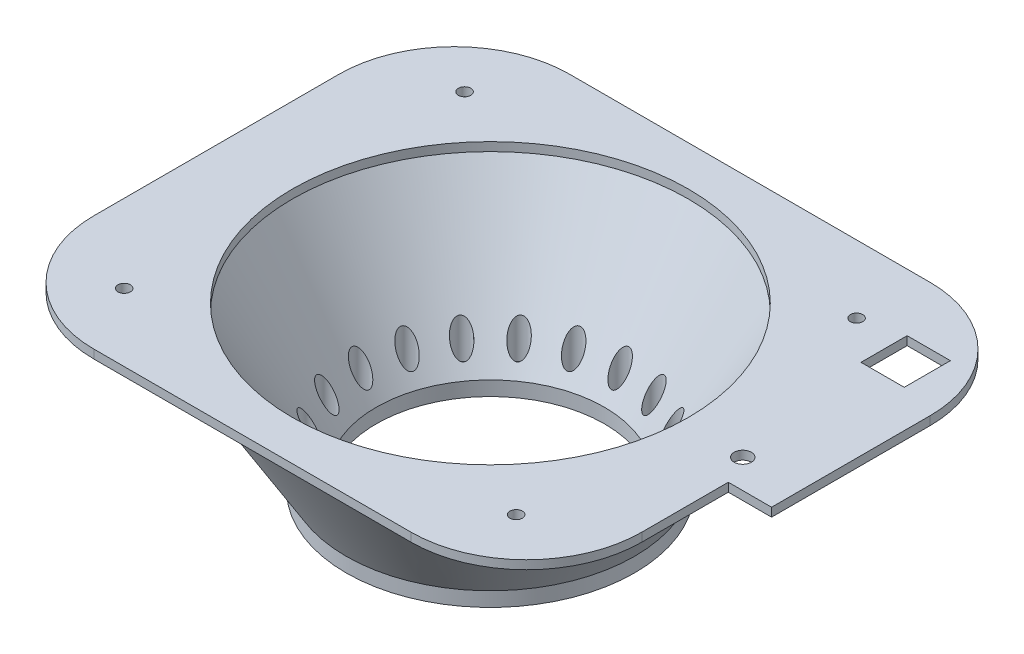
SolidWorks part; units mm, degrees
ref_plane "Front Plane" through (0, 0, 0) normal (0, 0, 1) x (1, 0, 0)
ref_plane "Top Plane" through (0, 0, 0) normal (0, 1, 0) x (1, 0, 0)
ref_plane "Right Plane" through (0, 0, 0) normal (1, 0, 0) x (0, 0, -1)
sketch "Sketch4" plane through (0, 0, 0) normal (0, 1, 0) x (1, 0, 0)
  line L0 (0, -45) -> (0, 45) construction
  line L1 (0, 0) -> (0, -45) construction
  circle A0 centre (0, 0) radius 39.565
  circle A1 centre (0, 0) radius 50
  circle A6 centre (0, -45) radius 1.75
  circle A7 centre (-13.9058, -42.7975) radius 1.75
  circle A8 centre (-26.4503, -36.4058) radius 1.75
  circle A9 centre (-36.4058, -26.4503) radius 1.75
  circle A10 centre (-42.7975, -13.9058) radius 1.75
  circle A11 centre (-45, 0) radius 1.75
  circle A12 centre (-42.7975, 13.9058) radius 1.75
  circle A13 centre (-36.4058, 26.4503) radius 1.75
  circle A14 centre (-26.4503, 36.4058) radius 1.75
  circle A15 centre (-13.9058, 42.7975) radius 1.75
  circle A16 centre (0, 45) radius 1.75
  circle A17 centre (13.9058, 42.7975) radius 1.75
  circle A18 centre (26.4503, 36.4058) radius 1.75
  circle A19 centre (36.4058, 26.4503) radius 1.75
  circle A20 centre (42.7975, 13.9058) radius 1.75
  circle A21 centre (45, 0) radius 1.75
  circle A22 centre (42.7975, -13.9058) radius 1.75
  circle A23 centre (36.4058, -26.4503) radius 1.75
  circle A24 centre (26.4503, -36.4058) radius 1.75
  circle A25 centre (13.9058, -42.7975) radius 1.75
  point P5 (0, 0)
  dimension "D1" = 79.13
  dimension "D3" = 100
  dimension "D5" = 3.5
  dimension "D2" = 90
  dimension "D7" = 45
  dimension "D6" = 20
extrude "Boss-Extrude3" add sketch "Sketch4" along normal blind 5
sketch "Sketch6" plane through (0, 0, 0) normal (1, 0, 0) x (0, 0, -1)
  line L0 (-50, 5) -> (-79.0628, 53)
  line L2 (-50, 5) -> (-39.565, 5)
  line L3 (-39.565, 5) -> (-68.6278, 53)
  line L5 (-68.6278, 53) -> (-79.0628, 53)
  dimension "D1" = 18.6278
  dimension "D2" = 48
ref_plane "Plane1" through (0, 15, 0) normal (0, 1, 0) x (1, 0, 0)
ref_axis "Axis1" through (0, 0, 0) along (0, 1, 0)
revolve "Revolve1" add sketch "Sketch6" angle 360 about axis through (0, 0, 0) along (0, 1, 0)
sketch "Sketch7" plane through (0, 53, 0) normal (0, 1, 0) x (1, 0, 0)
  line L1 (-95, 82.5) -> (95, 82.5)
  line L2 (-95, 82.5) -> (-95, -82.5)
  line L3 (-95, -82.5) -> (95, -82.5)
  line L4 (95, 82.5) -> (95, -82.5)
  line L5 (-95, 82.5) -> (95, -82.5) construction
  line L6 (-95, -82.5) -> (95, 82.5) construction
  circle A0 centre (0, 0) radius 68.6289
  circle A1 centre (-67.953, 59.0118) radius 2.15
  circle A2 centre (67.953, 59.0118) radius 2.15
  circle A3 centre (67.953, -59.0118) radius 2.15
  circle A4 centre (-67.953, -59.0118) radius 2.15
  point P4 (0, 0)
  dimension "D5" = 4.3
  dimension "D1" = 190
  dimension "D2" = 165
  dimension "D3" = 90
  dimension "D4" = 90
extrude "Boss-Extrude4" add sketch "Sketch7" along normal blind 3
fillet "Fillet1" radius 40 4 edges at (95, 54.5, -82.5) (95, 54.5, 82.5) (-95, 54.5, 82.5) (-95, 54.5, -82.5)
sketch "Sketch8" plane through (0, 0, 0) normal (0, -1, 0) x (1, 0, 0)
  line L0 (0, 0) -> (0, -45) construction
  circle A0 centre (0, -45) radius 3
  circle A1 centre (-13.9058, -42.7975) radius 3
  circle A2 centre (-26.4503, -36.4058) radius 3
  circle A3 centre (-36.4058, -26.4503) radius 3
  circle A4 centre (-42.7975, -13.9058) radius 3
  circle A5 centre (-45, 0) radius 3
  circle A6 centre (-42.7975, 13.9058) radius 3
  circle A7 centre (-36.4058, 26.4503) radius 3
  circle A8 centre (-26.4503, 36.4058) radius 3
  circle A9 centre (-13.9058, 42.7975) radius 3
  circle A10 centre (0, 45) radius 3
  circle A11 centre (13.9058, 42.7975) radius 3
  circle A12 centre (26.4503, 36.4058) radius 3
  circle A13 centre (36.4058, 26.4503) radius 3
  circle A14 centre (42.7975, 13.9058) radius 3
  circle A15 centre (45, 0) radius 3
  circle A16 centre (42.7975, -13.9058) radius 3
  circle A17 centre (36.4058, -26.4503) radius 3
  circle A18 centre (26.4503, -36.4058) radius 3
  circle A19 centre (13.9058, -42.7975) radius 3
  dimension "D1" = 20
  dimension "D3" = 6
  dimension "D2" = 45
extrude "Cut-Extrude1" cut sketch "Sketch8" against normal through all from offset 5 offset against normal yes
sketch "Sketch9" plane through (0, 56, 0) normal (0, 1, 0) x (1, 0, 0)
  line L0 (-55, -82.5) -> (55, -82.5) construction
  line L1 (74, -1.5) -> (80, -1.5)
  line L2 (74, -1.5) -> (74, -11.5)
  line L3 (74, -11.5) -> (80, -11.5)
  line L4 (80, -1.5) -> (80, -11.5)
  line L5 (95, -42.5) -> (95, 42.5) construction
  dimension "D1" = 6
  dimension "D2" = 10
  dimension "D3" = 71
  dimension "D4" = 15
extrude "Boss-Extrude5" [suppressed] add sketch "Sketch9" along normal blind 5
sketch "Sketch10" [suppressed] plane through (0, 0, 11.5) normal (0, 0, 1) x (1, 0, 0)
  line L0 (77, 58.5) -> (77, 61) construction
  line L1 (74, 61) -> (80, 61) construction
  line L2 (95, 56) -> (55, 56) construction
  circle A0 centre (77, 58.5) radius 1.75
  dimension "D1" = 3.5
  dimension "D2" = 2.5
extrude "Cut-Extrude2" [suppressed] cut sketch "Sketch10" against normal up to next
sketch "Sketch11" plane through (0, 56, 0) normal (0, 1, 0) x (1, 0, 0)
  line L0 (-55, -82.5) -> (55, -82.5) construction
  line L1 (55, 82.5) -> (110, 82.5)
  line L2 (55, 82.5) -> (55, 68.6019)
  line L3 (78.9066, -12.5) -> (110, -12.5)
  line L4 (110, 82.5) -> (110, -12.5)
  line L6 (95, -42.5) -> (95, 42.5) construction
  line L7 (55, 68.6019) -> (78.9066, 68.6019)
  line L8 (78.9066, 68.6019) -> (78.9066, -12.5)
  arc A0 (95, 42.5) -> (55, 82.5) centre (55, 42.5) ccw construction
  dimension "D2" = 70
  dimension "D4" = 15
extrude "Boss-Extrude7" add sketch "Sketch11" against normal up to surface (3 mm away) up to face at (0, 53, -79.0628)
sketch "Sketch12" plane through (0, 56, 0) normal (0, 1, 0) x (1, 0, 0)
  line L2 (-55, -82.5) -> (55, -82.5) construction
  line L3 (95, -42.5) -> (95, -12.5) construction
  circle A0 centre (90, -2.5) radius 3
  dimension "D1" = 6
  dimension "D2" = 5
  dimension "D3" = 80
extrude "Cut-Extrude3" cut sketch "Sketch12" against normal through all
fillet "Fillet2" radius 40 1 edges at (110, 54.5, -82.5)
sketch "Sketch13" plane through (0, 56, 0) normal (0, 1, 0) x (1, 0, 0)
  line L0 (70, 82.5) -> (-55, 82.5) construction
  line L1 (82, 62.5) -> (97, 62.5)
  line L2 (82, 62.5) -> (82, 46.5)
  line L3 (82, 46.5) -> (97, 46.5)
  line L4 (97, 62.5) -> (97, 46.5)
  line L5 (110, -12.5) -> (110, 42.5) construction
  dimension "D1" = 15
  dimension "D2" = 20
  dimension "D3" = 13
  dimension "D4" = 16
extrude "Cut-Extrude4" cut sketch "Sketch13" against normal through all
